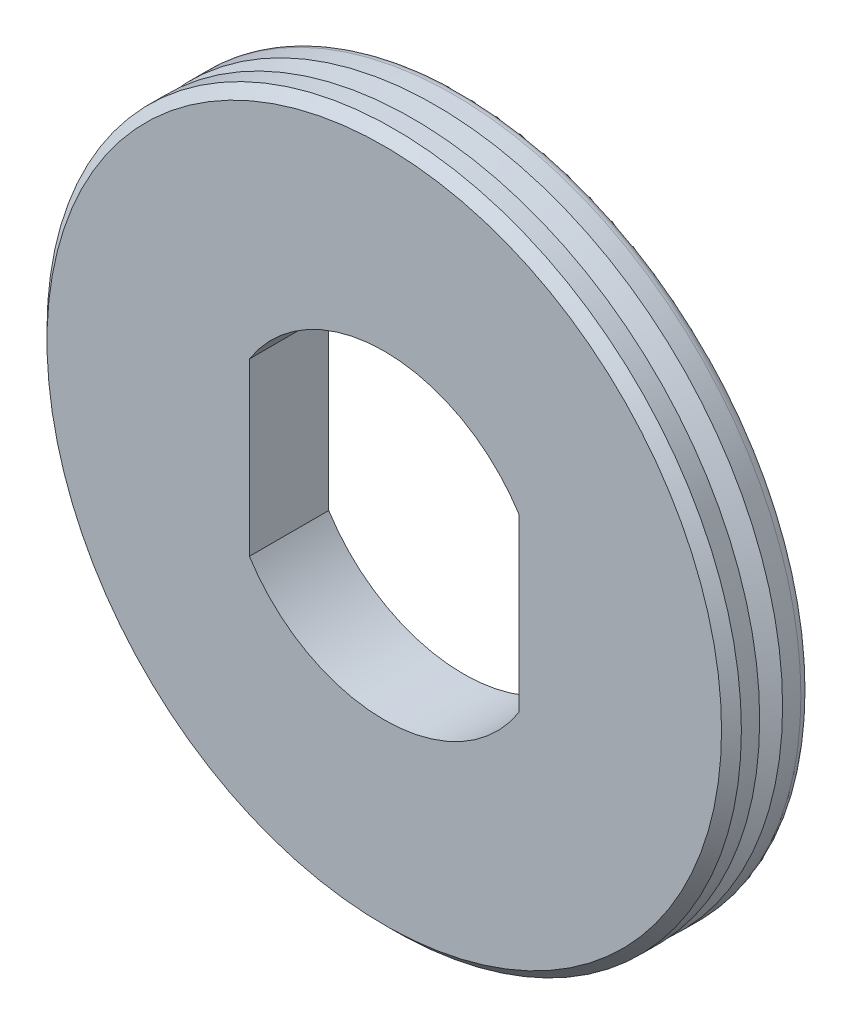
SolidWorks part; units mm, degrees
ref_plane "Спереди" through (0, 0, 0) normal (0, 0, 1) x (1, 0, 0)
ref_plane "Сверху" through (0, 0, 0) normal (0, 1, 0) x (1, 0, 0)
ref_plane "Справа" through (0, 0, 0) normal (1, 0, 0) x (0, 0, -1)
sketch "Эскиз1" plane through (0, 0, 0) normal (0, 0, 1) x (1, 0, 0)
  line L2 (6.8, 4.3084) -> (6.8, -4.3084)
  line L4 (-6.8, 4.3084) -> (-6.8, -4.3084)
  circle A0 centre (0, 0) radius 17.5
  arc A1 (-6.8, -4.3084) -> (6.8, -4.3084) centre (0, 0) ccw
  arc A2 (6.8, 4.3084) -> (-6.8, 4.3084) centre (0, 0) ccw
  point P6 (6.8, 0)
  point P8 (-6.8, 0)
  point P9 (0, -8.05)
  point P11 (0, 8.05)
  dimension "D1" = 8.05
  dimension "D2" = 35
  dimension "D3" = 13.6
extrude "Бобышка-Вытянуть2" add sketch "Эскиз1" along normal mid plane 4
sketch "Эскиз2" plane through (0, 0, 0) normal (1, 0, 0) x (0, 0, -1)
  line L0 (-2, 17.5) -> (-2, -17.5) construction
  line L1 (-2, 17.5) -> (-2, -17.5) construction
  line L2 (-0.5774, 17.5) -> (0.5774, 17.5)
  line L3 (0.5774, 17.5) -> (0, 16.5)
  line L4 (0, 16.5) -> (-0.5774, 17.5)
  line L5 (-3.2487, 0) -> (4.3764, 0) construction
  point P5 (0, 17.5)
  dimension "D1" = 1
  dimension "D2" = 60
revolve "Вырез-Повернуть1" cut sketch "Эскиз2" angle 360 about L5
fillet "Скругление1" [suppressed] radius 0.2
chamfer "Фаска1" distance 0.5 angle 45 1 edges at (17.5, 0, 2)
fillet "Скругление2" radius 0.5 1 edges at (17.5, 0, -2)
